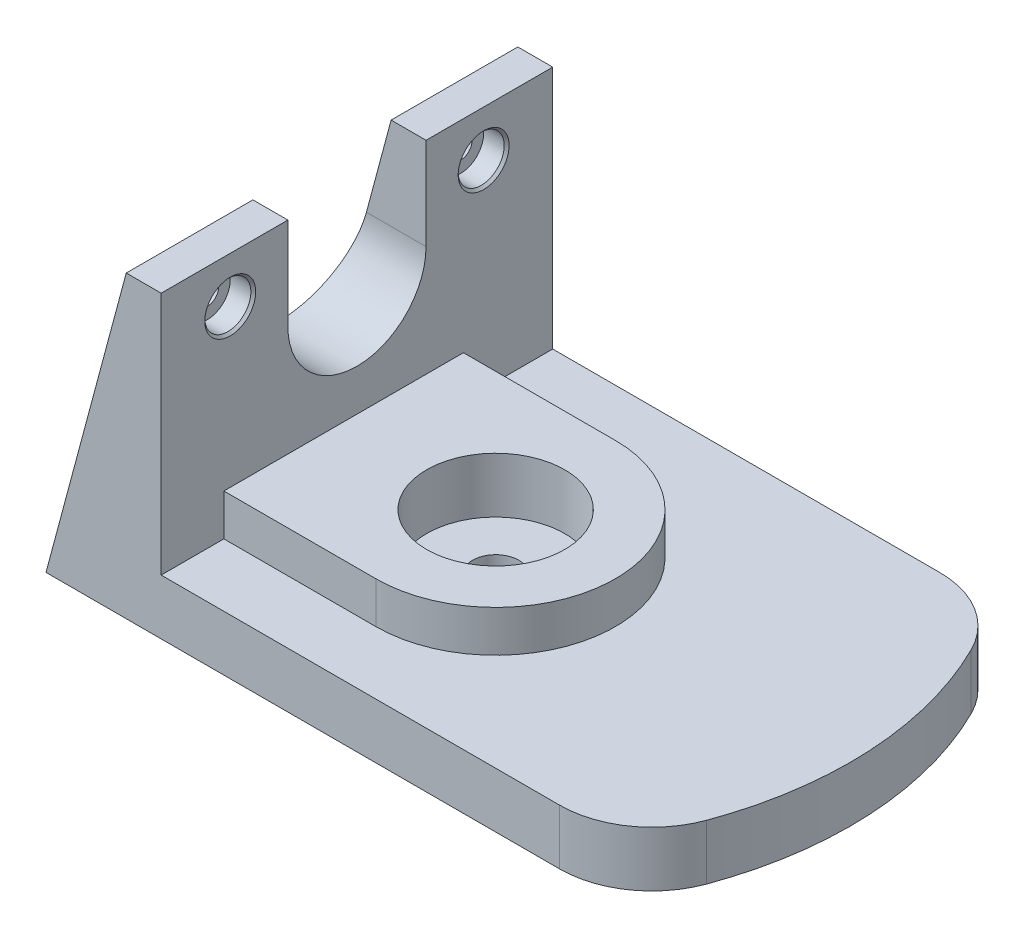
SolidWorks part; units mm, degrees
ref_plane "Přední rovina" through (0, 0, 0) normal (0, 0, 1) x (1, 0, 0)
ref_plane "Horní rovina" through (0, 0, 0) normal (0, 1, 0) x (1, 0, 0)
ref_plane "Pravá rovina" through (0, 0, 0) normal (1, 0, 0) x (0, 0, -1)
sketch "Skica1" plane through (0, 0, 0) normal (0, 0, 1) x (1, 0, 0)
  line L0 (0, 0) -> (135, 0)
  line L1 (135, 0) -> (135, 12)
  line L2 (135, 12) -> (25, 12)
  line L3 (25, 12) -> (25, 65)
  line L4 (25, 65) -> (17.4167, 65)
  line L5 (17.4167, 65) -> (0, 0)
  point P9 (24.0245, 0)
  point P10 (0.2584, 1.1119)
  dimension "D1" = 135
  dimension "D2" = 12
  dimension "D3" = 25
  dimension "D4" = 65
  dimension "D5" = 15
extrude "Přidat vysunutím1" add sketch "Skica1" along normal mid plane 85 contours L3 L4 L5 L0 L1 L2
sketch "Skica2" plane through (0, 12, 0) normal (0, 1, 0) x (1, 0, 0)
  line L0 (135, 42.5) -> (25, 42.5) construction
  line L1 (135, -42.5) -> (25, -42.5) construction
  line L2 (135, -42.5) -> (135, 42.5) construction
  arc A0 (120.2031, 42.5) -> (124.0275, -42.5) centre (58, -2.8848) cw
extrude "Odebrat vysunutím1" cut sketch "Skica2" against normal through all both and the other way through all
sketch "Skica3" plane through (0, 12, 0) normal (0, 1, 0) x (1, 0, 0)
  line L0 (25, 23.1152) -> (58, 23.1152)
  line L2 (25, -42.5) -> (25, 42.5) construction
  line L3 (58, -28.8848) -> (25, -28.8848)
  line L4 (17.4167, -42.5) -> (0, -42.5) construction
  line L5 (25, -28.8848) -> (25, 23.1152)
  arc A0 (58, 23.1152) -> (58, -28.8848) centre (58, -2.8848) cw
  arc A1 (124.0275, -42.5) -> (120.2031, 42.5) centre (58, -2.8848) ccw construction
  dimension "D1" = 85
  dimension "D2" = 26
extrude "Přidat vysunutím2" add sketch "Skica3" along normal blind 9 contours L5 L0 A0 L3
sketch "Skica4" plane through (25, 0, 0) normal (1, 0, 0) x (0, 0, -1)
  line L0 (15, 65) -> (15, 45)
  line L1 (-42.5, 65) -> (42.5, 65) construction
  line L2 (-15, 45) -> (-15, 65)
  line L3 (-15, 65) -> (15, 65)
  arc A0 (15, 45) -> (-15, 45) centre (0, 45) cw
  point P6 (0, 0)
extrude "Odebrat vysunutím2" cut sketch "Skica4" against normal through all and the other way through all contours L3 L0 A0 L2
sketch "Skica6" plane through (25, 0, 0) normal (1, 0, 0) x (0, 0, -1)
  line L0 (-42.5, 65) -> (-15, 65) construction
  line L1 (27.5, 55) -> (-27.5, 55)
  line L2 (27.5, 55) -> (27.5, 65)
  line L3 (27.5, 65) -> (-27.5, 65)
  line L4 (-27.5, 55) -> (-27.5, 65)
  line L5 (27.5, 55) -> (-27.5, 65) construction
  line L6 (27.5, 65) -> (-27.5, 55) construction
  point P0 (0, 60)
  point P2 (27.5, 55)
  point P4 (-27.5, 55)
hole_wizard "Válcové zahloubení pro M5 šrouby s válcovou hlavou zaoblenou1" positions "Skica6" profile "Skica9" counterbore size "M5" standard "ANSI Metric" end condition through all
sketch "Skica9" plane through (25, 60, 0) normal (0, 1, 0) x (0, 0, -1)
  line L0 (0, 0) -> (0, 25)
  line L1 (0, 25) -> (2.5, 25)
  line L3 (2.5, 25) -> (2.5, 5)
  line L4 (5, 5) -> (2.5, 5)
  line L5 (5, 5) -> (5, 0.525)
  line L6 (5, 0.525) -> (5.525, 0)
  line L7 (5.525, 0) -> (0, 0)
  line L8 (-5, 0.525) -> (-5.525, 0) construction
  line L11 (0, -6.35) -> (0, 107.95) construction
  dimension "Průměr díry skrz" = 5
  dimension "Hloubka díry skrz" = 25
  dimension "Průměr válcového zahloubení" = 10
  dimension "Hloubka válcového zahloubení" = 5
  dimension "Průměr blíz. kuž. zahloubení" = 11.05
  dimension "Úhel blíz. kuž. zahloubení" = 90
hole_wizard "Válcové zahloubení pro M10 šrouby s válcovou hlavou zaoblenou3" positions "Skica17" profile "Skica18" counterbore size "M10" standard "ANSI Metric" end condition through all
sketch "Skica17" plane through (0, 21, 0) normal (0, 1, 0) x (1, 0, 0)
  point P0 (58, -2.8848)
sketch "Skica18" plane through (58, 21, 2.8848) normal (1, 0, 0) x (0, 0, 1)
  line L0 (0, 0) -> (0, 21)
  line L1 (0, 21) -> (5, 21)
  line L3 (5, 21) -> (5, 12)
  line L4 (5, 12) -> (15, 12)
  line L5 (15, 12) -> (15, 0)
  line L7 (15, 0) -> (0, 0)
  line L11 (0, -6.35) -> (0, 107.95) construction
  dimension "Průměr díry skrz" = 10
  dimension "Hloubka díry skrz" = 21
  dimension "Průměr válcového zahloubení" = 30
  dimension "Hloubka válcového zahloubení" = 12
fillet "Zaoblit1" radius 20 2 edges at (120.2031, 6, -42.5) (124.0275, 6, 42.5)
